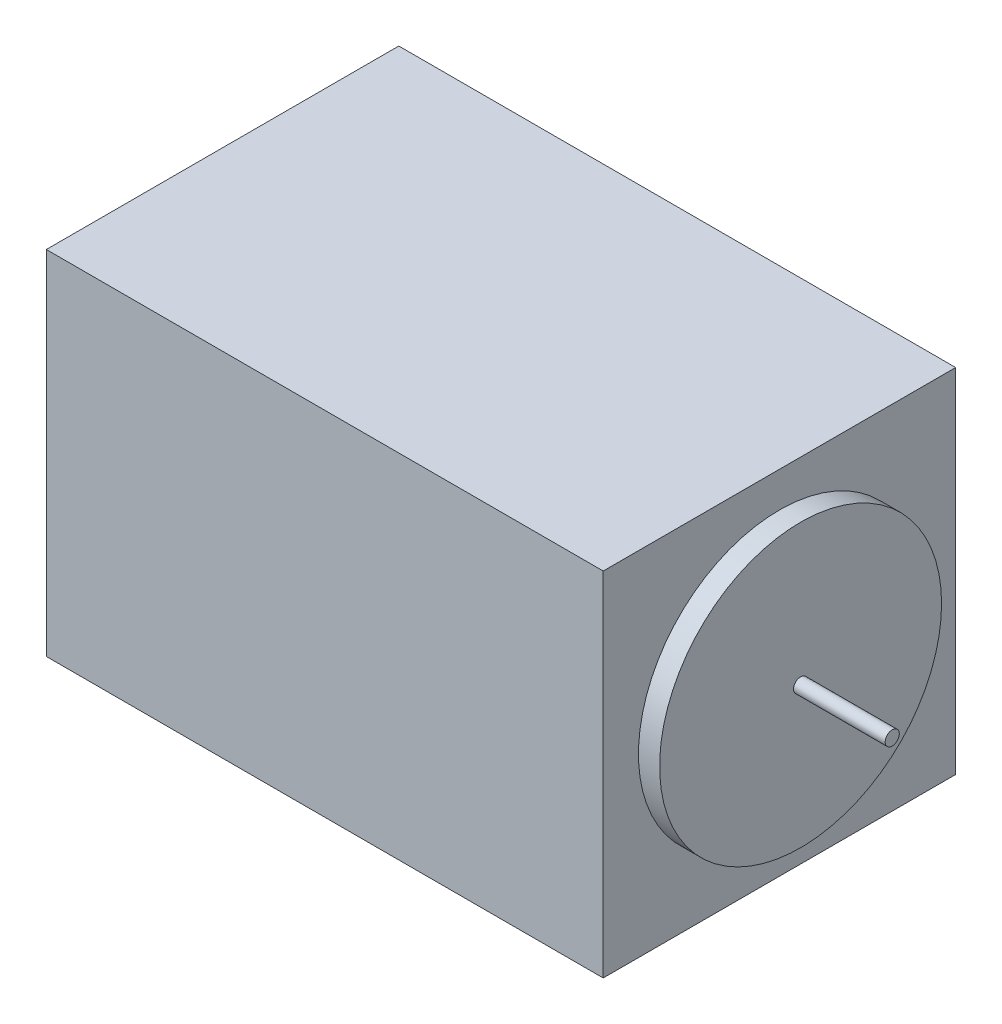
SolidWorks part; units mm, degrees
ref_plane "前视基准面" through (0, 0, 0) normal (0, 0, 1) x (1, 0, 0)
ref_plane "上视基准面" through (0, 0, 0) normal (0, 1, 0) x (1, 0, 0)
ref_plane "右视基准面" through (0, 0, 0) normal (1, 0, 0) x (0, 0, -1)
sketch "草图1" plane through (0, 0, 0) normal (1, 0, 0) x (0, 0, -1)
  line L1 (-25, 25) -> (25, 25)
  line L2 (-25, 25) -> (-25, -25)
  line L3 (-25, -25) -> (25, -25)
  line L4 (25, 25) -> (25, -25)
  line L5 (-25, 25) -> (25, -25) construction
  line L6 (-25, -25) -> (25, 25) construction
  point P0 (0, 0)
  dimension "D1" = 50
  dimension "D2" = 50
extrude "凸台-拉伸1" add sketch "草图1" along normal blind 79
sketch "草图2" plane through (0, 0, 0) normal (1, 0, 0) x (0, 0, -1)
  circle A0 centre (0, 0) radius 20
  point P3 (0, 0)
extrude "凸台-拉伸2" add sketch "草图2" along normal blind 82
sketch "草图3" plane through (0, 0, 0) normal (1, 0, 0) x (0, 0, -1)
  circle A0 centre (0, 0) radius 1
extrude "凸台-拉伸3" add sketch "草图3" along normal blind 95
